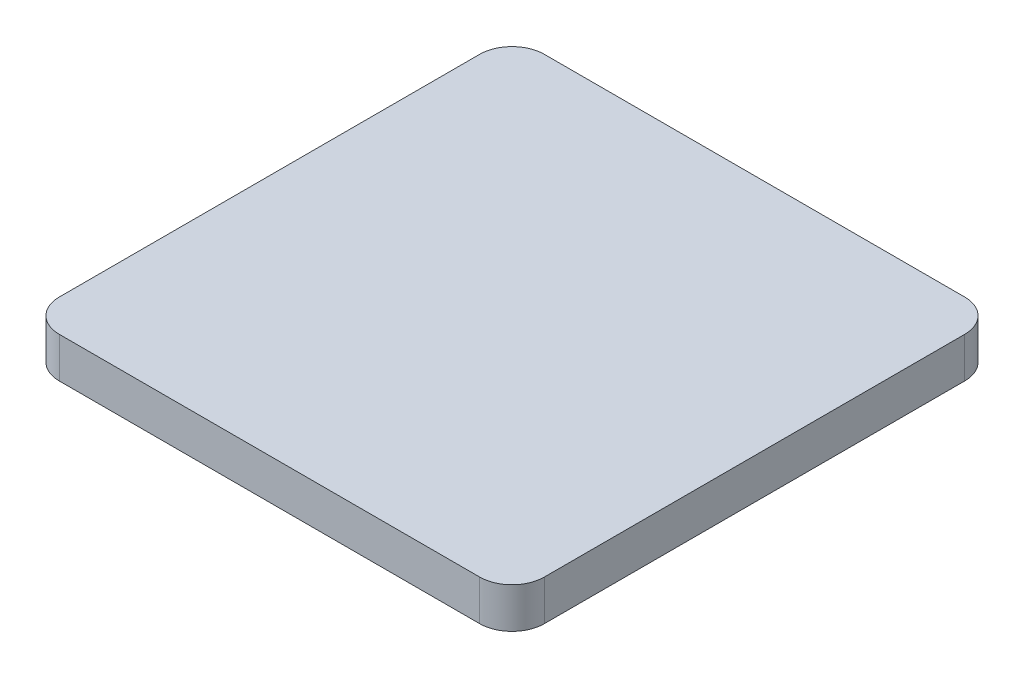
SolidWorks part; units mm, degrees
ref_plane "前视基准面" through (0, 0, 0) normal (0, 0, 1) x (1, 0, 0)
ref_plane "上视基准面" through (0, 0, 0) normal (0, 1, 0) x (1, 0, 0)
ref_plane "右视基准面" through (0, 0, 0) normal (1, 0, 0) x (0, 0, -1)
sketch "草图1" plane through (0, 0, 0) normal (0, 1, 0) x (1, 0, 0)
  line L1 (60, 60) -> (-60, 60)
  line L2 (60, 60) -> (60, -60)
  line L3 (60, -60) -> (-60, -60)
  line L4 (-60, 60) -> (-60, -60)
  line L5 (60, 60) -> (-60, -60) construction
  line L6 (60, -60) -> (-60, 60) construction
  point P0 (0, 0)
  dimension "D1" = 120
extrude "凸台-拉伸1" add sketch "草图1" along normal blind 10
fillet "圆角1" radius 8 4 edges at (-60, 5, -60) (60, 5, -60) (60, 5, 60) (-60, 5, 60)
sketch "草图2" plane through (0, 10, 0) normal (0, 1, 0) x (1, 0, 0)
  circle A0 centre (0, 0) radius 29.0962
